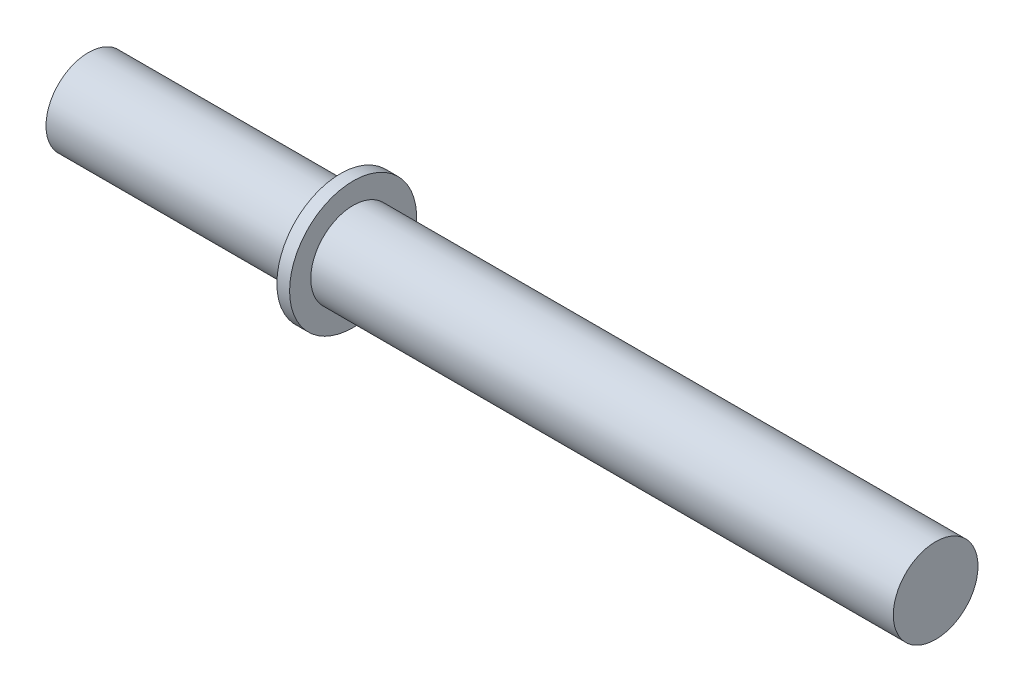
SolidWorks part; units mm, degrees
ref_plane "Alzado" through (0, 0, 0) normal (0, 0, 1) x (1, 0, 0)
ref_plane "Planta" through (0, 0, 0) normal (0, 1, 0) x (1, 0, 0)
ref_plane "Vista lateral" through (0, 0, 0) normal (1, 0, 0) x (0, 0, -1)
sketch "Croquis1" plane through (0, 0, 0) normal (1, 0, 0) x (0, 0, -1)
  circle A0 centre (0, 0) radius 10
  dimension "D1" = 20
extrude "Saliente-Extruir1" add sketch "Croquis1" along normal blind 200
ref_plane "Plano1" through (62.5, 0, 0) normal (-1, 0, 0) x (0, 0, 1)
sketch "Croquis2" plane through (62.5, 0, 0) normal (-1, 0, 0) x (0, 0, 1)
  circle A0 centre (0, 0) radius 15
  dimension "D1" = 30
extrude "Saliente-Extruir2" add sketch "Croquis2" along normal blind 3
